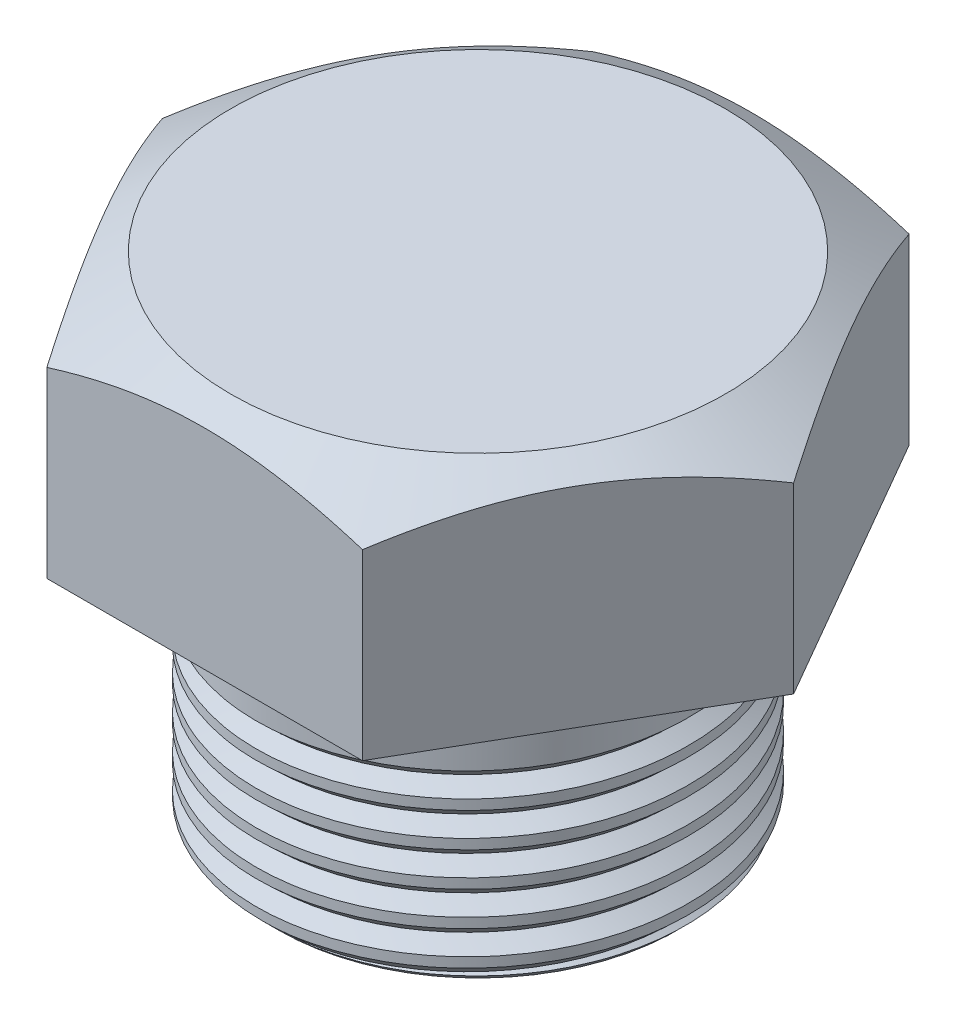
SolidWorks part; units mm, degrees
material "Ductile Iron"
ref_plane "Front Plane" through (0, 0, 0) normal (0, 0, 1) x (1, 0, 0)
ref_plane "Top Plane" through (0, 0, 0) normal (0, 1, 0) x (1, 0, 0)
ref_plane "Right Plane" through (0, 0, 0) normal (1, 0, 0) x (0, 0, -1)
sketch "Sketch1" plane through (0, 0, 0) normal (0, 1, 0) x (1, 0, 0)
  circle A0 centre (0, 0) radius 12.65
  dimension "D1" = 25.3
extrude "Boss-Extrude1" add sketch "Sketch1" along normal blind 15.4
sketch "Sketch2" plane through (0, 15.4, 0) normal (0, 1, 0) x (1, 0, 0)
  line L1 (-18.4752, 0) -> (-9.2376, -16)
  line L2 (-9.2376, -16) -> (9.2376, -16)
  line L3 (9.2376, -16) -> (18.4752, 0)
  line L4 (18.4752, 0) -> (9.2376, 16)
  line L5 (9.2376, 16) -> (-9.2376, 16)
  line L6 (-9.2376, 16) -> (-18.4752, 0)
  circle A0 centre (0, 0) radius 16 construction
  dimension "D1" = 32
extrude "Boss-Extrude2" add sketch "Sketch2" along normal blind 13.2
sketch "Sketch3" plane through (0, 0, 0) normal (0, 0, 1) x (1, 0, 0)
  line L0 (-14.4752, 28.6) -> (-18.4752, 28.6)
  line L1 (-18.4752, 28.6) -> (-9.2376, 28.6) construction
  line L2 (-18.4752, 28.6) -> (-18.4752, 26.1)
  line L3 (-18.4752, 28.6) -> (-18.4752, 15.4) construction
  line L4 (-18.4752, 26.1) -> (-14.4752, 28.6)
  dimension "D1" = 4
  dimension "D2" = 2.5
sweep "Cut-Sweep1" cut profiles "Sketch3" path edge at (0, 15.4, 12.65)
sketch "Sketch4" plane through (0, 0, 0) normal (0, -1, 0) x (1, 0, 0)
  circle A0 centre (0, 0) radius 10
  dimension "D1" = 20
extrude "Cut-Extrude1" cut sketch "Sketch4" against normal blind 24
sketch "Sketch5" plane through (0, 0, 0) normal (0, -1, 0) x (1, 0, 0)
  circle A0 centre (0, 0) radius 12.65
  dimension "D1" = 25.3
chamfer "Chamfer1" distance 1 angle 45 1 edges at (0, 0, 12.65)
curve "Helix/Spiral1" pitch 2 height 11 turns 5.5
ref_plane "Plane1" through (0, 0, 8.9449) normal (0, 0, 1) x (1, 0, 0)
sketch "Sketch6" plane through (0, 0, 8.9449) normal (0, 0, 1) x (1, 0, 0)
  line L0 (-7.8, 0) -> (-9.245, 0.8955)
  line L1 (-9.245, 0.8955) -> (-9.245, -0.8955)
  line L2 (-9.245, -0.8955) -> (-7.8, 0)
  line L3 (0, 0) -> (0, 5.8173) construction
  line L4 (-11.65, 0) -> (11.65, 0) construction
  dimension "D1" = 7.8
  dimension "D2" = 1.7
  dimension "D4" = 0.8955
  dimension "D5" = 0.8955
sweep "Cut-Sweep2" cut profiles "Sketch6" path "Helix/Spiral1"
sketch "Sketch7" plane through (0, 0, -8.9449) normal (0, 0, 1) x (1, 0, 0)
  line L3 (8.9449, 11.7095) -> (7.8, 11)
  line L4 (7.8, 11) -> (8.9449, 10.2905)
  line L5 (8.9449, 10.2905) -> (8.9449, 11.7095)
  line L6 (8.9449, 11.7095) -> (7.8, 11)
  line L7 (7.8, 11) -> (8.9449, 10.2905)
  line L8 (8.9449, 10.2905) -> (8.9449, 11.7095)
  dimension "D1" = 0
revolve "Cut-Revolve1" cut sketch "Sketch7" angle 360 about L8
